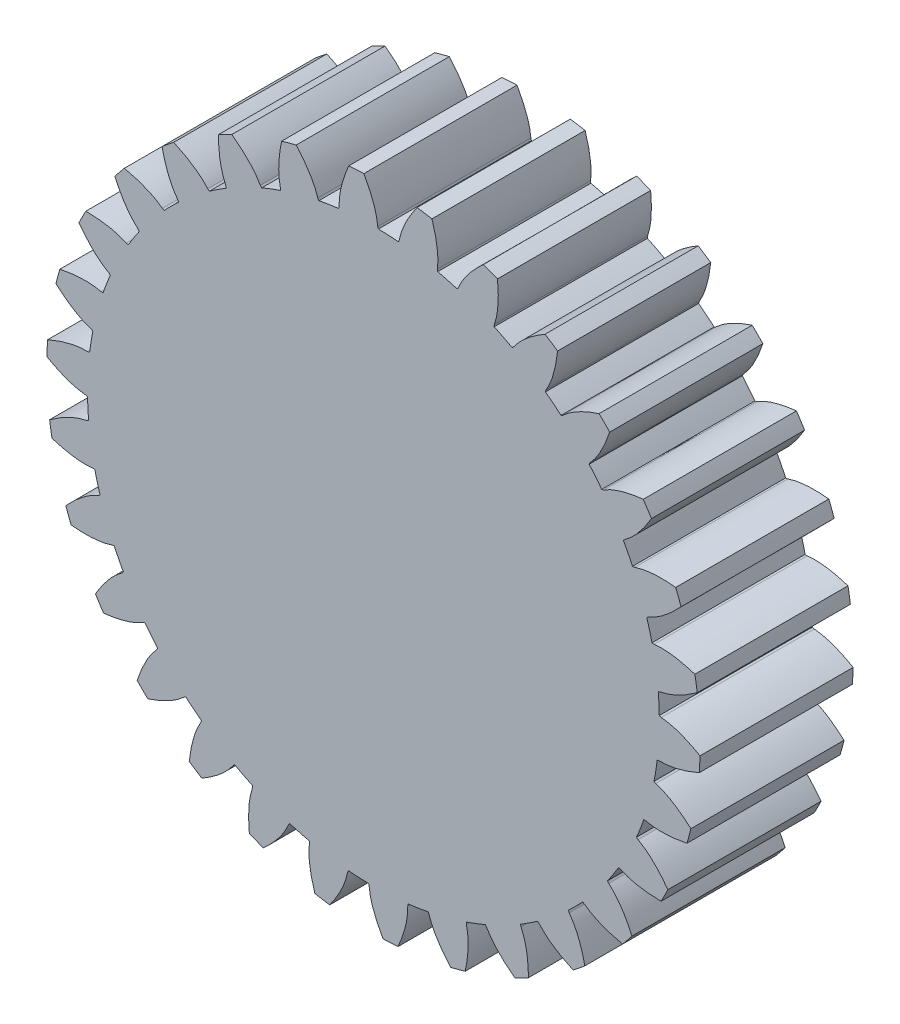
SolidWorks part; units mm, degrees
ref_plane "Front Plane" through (0, 0, 0) normal (0, 0, 1) x (1, 0, 0)
ref_plane "Top Plane" through (0, 0, 0) normal (0, 1, 0) x (1, 0, 0)
ref_plane "Right Plane" through (0, 0, 0) normal (1, 0, 0) x (0, 0, -1)
sketch "involute" plane through (0, 0, 0) normal (0, 0, 1) x (1, 0, 0)
  line L0 (0, 0) -> (0, 19.05) construction
  line L1 (0, 0) -> (-6.1226, 16.8216) construction
  line L2 (-6.1226, 16.8216) -> (0, 19.05) construction
  line L3 (-8.9292, 15.5152) -> (-0.5956, 20.3113) construction
  line L4 (-8.1296, 15.9487) -> (-0.3736, 19.9022) construction
  line L5 (-7.2112, 16.3844) -> (-0.1738, 19.4818) construction
  line L6 (0, 19.05) -> (-0.1738, 19.4818) construction
  line L7 (-0.1738, 19.4818) -> (-0.3736, 19.9022) construction
  line L8 (-0.3736, 19.9022) -> (-0.5956, 20.3113) construction
  circle A0 centre (0, 0) radius 19.05 construction
  arc A1 (0.2668, 17.8992) -> (-8.9292, 15.5152) centre (0, 0) ccw construction
  circle A2 centre (0, 0) radius 20.32 construction
  arc A3 (-6.1226, 16.8216) -> (0.2668, 17.8992) centre (0, 0) cw construction
  arc A4 (0.2668, 17.8992) -> (-8.1296, 15.9487) centre (0, 0) ccw construction
  arc A5 (0.2668, 17.8992) -> (-7.2112, 16.3844) centre (0, 0) ccw construction
  dimension "D1" = 38.1
  dimension "D4" = 40.64
  dimension "D2" = 20
sketch "undercut" plane through (0, 0, 0) normal (0, 0, 1) x (1, 0, 0)
  line L0 (0.2668, 17.8992) -> (0.3088, 17.7773) construction
  line L1 (-9.5271, 17.9482) -> (10.1447, 17.6065) construction
  line L2 (0.2668, 17.8992) -> (0.2743, 17.8677) construction
  line L3 (-7.7205, 18.7962) -> (11.8229, 16.5264) construction
  line L4 (-8.5193, 18.4478) -> (11.1034, 17.0181) construction
  line L5 (0.2933, 17.8058) -> (0.2668, 17.8992) construction
  line L6 (0.3088, 17.7773) -> (0.2933, 17.8058) construction
  line L7 (11.5132, 16.7436) -> (-8.0691, 18.6492) construction
  line L8 (0.2829, 17.8364) -> (0.2668, 17.8992) construction
  line L9 (0.2829, 17.8364) -> (0.2933, 17.8058) construction
  line L10 (0.2743, 17.8677) -> (0.2829, 17.8364) construction
  circle A0 centre (0, 0) radius 20.32 construction
  dimension "D1" = 70
  dimension "D2" = 17.78
  dimension "D3" = 70
  dimension "D4" = 17.78
  dimension "D5" = 70
  dimension "D6" = 17.78
  dimension "D7" = 70
  dimension "D8" = 17.78
sketch "Sketch2" plane through (0, 0, 0) normal (0, 0, 1) x (1, 0, 0)
  circle A0 centre (0, 0) radius 20.32
extrude "Boss-Extrude1" add sketch "Sketch2" along normal mid plane 9.525
sketch "Sketch3" plane through (0, 0, 4.7625) normal (0, 0, 1) x (1, 0, 0)
  line L0 (0, 19.05) -> (0, 0) construction
  line L1 (0, 0) -> (0.9305, 17.7556) construction
  arc A0 (0.3088, 17.7773) -> (1.5512, 17.7122) centre (0, 0) cw
  arc A1 (-0.5956, 20.3113) -> (2.7155, 20.1377) centre (0, 0) cw
  spline S0 degree 3 poles (-0.5956, 20.3113) (-0.4408, 20.0423) (-0.0483, 19.2766) (0.2173, 18.4534) (0.2668, 17.8992) knots 0 0 0 0 0.361135 1 1 1 1
  spline S1 degree 3 poles (0.2668, 17.8992) (0.2713, 17.878) (0.2823, 17.8364) (0.2958, 17.7951) (0.3088, 17.7773) knots 0 0 0 0 0.5 1 1 1 1
  spline S2 degree 3 poles (2.7155, 20.1377) (2.5333, 19.8865) (2.063, 19.166) (1.7128, 18.375) (1.6056, 17.829) knots 0 0 0 0 0.361135 1 1 1 1
  spline S3 degree 3 poles (1.6056, 17.829) (1.5989, 17.8084) (1.5836, 17.7682) (1.5659, 17.7285) (1.5512, 17.7122) knots 0 0 0 0 0.5 1 1 1 1
  dimension "D1" = 3
extrude "Cut-Extrude1" cut sketch "Sketch3" against normal through all both and the other way through all
pattern_circular "CirPattern1" count 30 over 360 about axis through (0, 0, 4.7625) along (0, 0, -1) of "Cut-Extrude1"
equation "\"n\" = 30"
equation "\"dp\"= 20"
equation "\"a\"= 20"
equation "\"m\"= 1 / \"dp\""
equation "\"pd\"= \"n\" / \"dp\""
equation "\"add\"= \"m\""
equation "\"ded\"= 1.25 * \"m\""
equation "\"od\"= \"pd\" + 2 * \"add\""
equation "\"rd\"= \"pd\" - 2 * \"add\""
equation "\"D1@involute\" = \"pd\""
equation "\"D2@involute\" = \"a\""
equation "\"D4@involute\" = \"od\""
equation "\"D1@undercut\" = 90 - \"a\""
equation "\"D2@undercut\" = \"rd\" / 2"
equation "\"D3@undercut\" = 90 - \"a\""
equation "\"D4@undercut\" = \"D2@undercut\""
equation "\"D5@undercut\" = \"D3@undercut\""
equation "\"D6@undercut\" = \"D2@undercut\""
equation "\"D7@undercut\" = \"D3@undercut\""
equation "\"D8@undercut\" = \"D2@undercut\""
equation "\"D1@Sketch3\"=90/\"n\""
equation "\"D1@CirPattern1\"=\"n\""
